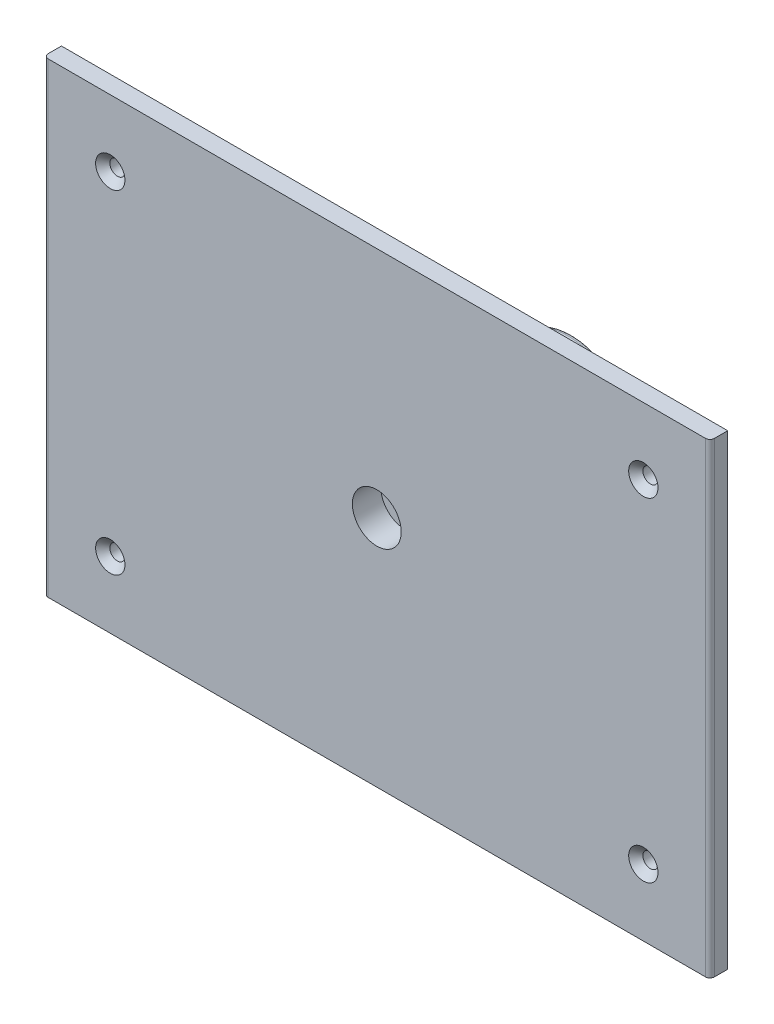
SolidWorks part; units mm, degrees
ref_plane "Front Plane" through (0, 0, 0) normal (0, 0, 1) x (1, 0, 0)
ref_plane "Top Plane" through (0, 0, 0) normal (0, 1, 0) x (1, 0, 0)
ref_plane "Right Plane" through (0, 0, 0) normal (1, 0, 0) x (0, 0, -1)
sketch "Sketch1" plane through (0, 0, 0) normal (0, 0, 1) x (1, 0, 0)
  line L1 (75, 52.5) -> (-75, 52.5)
  line L2 (75, 52.5) -> (75, -52.5)
  line L3 (75, -52.5) -> (-75, -52.5)
  line L4 (-75, 52.5) -> (-75, -52.5)
  line L5 (75, 52.5) -> (-75, -52.5) construction
  line L6 (75, -52.5) -> (-75, 52.5) construction
  point P0 (0, 0)
  dimension "D1" = 105
  dimension "D2" = 150
extrude "Boss-Extrude1" add sketch "Sketch1" along normal mid plane 4
hole_wizard "M3 Clearance Hole1" positions "Sketch3" profile "Sketch4" hole size "M3" standard "ISO" end condition through all
sketch "Sketch3" plane through (0, 0, -2) normal (0, 0, -1) x (-1, 0, 0)
  line L0 (0, 0) -> (0, 18.5081) construction
  line L2 (75, -52.5) -> (-75, -52.5) construction
  line L3 (-75, -52.5) -> (-75, 52.5) construction
  point P0 (-60, -37.5)
  point P2 (60, -37.5)
  dimension "D1" = 15
  dimension "D2" = 15
sketch "Sketch4" plane through (60, -37.5, -2) normal (1, 0, 0) x (0, 1, 0)
  line L0 (0, 0) -> (0, 4)
  line L1 (0, 4) -> (3.3, 4)
  line L2 (1.7, 2.4) -> (1.7, 0)
  line L5 (1.7, 0) -> (0, 0)
  line L7 (3.3, 4) -> (1.7, 2.4)
  line L8 (-3.3, 4) -> (-1.7, 2.4) construction
  line L11 (0, -6.35) -> (0, 107.95) construction
  dimension "Thru Hole Dia." = 3.4
  dimension "Thru Hole Depth" = 4
  dimension "Far C'Sink Dia." = 6.6
  dimension "Far C'Sink Angle" = 90
sketch "Sketch5" plane through (0, 0, -2) normal (0, 0, -1) x (-1, 0, 0)
  circle A0 centre (0, 0) radius 14
  dimension "D1" = 28
extrude "Boss-Extrude2" add sketch "Sketch5" along normal blind 40
hole_wizard "CBORE for M6 Hex Socket Head Cap Screw1" positions "Sketch6" profile "Sketch7" counterbore size "M6" standard "ISO" end condition up to next
sketch "Sketch6" plane through (0, 0, 2) normal (0, 0, 1) x (1, 0, 0)
  point P0 (0, 0)
sketch "Sketch7" plane through (0, 0, 2) normal (1, 0, 0) x (0, -1, 0)
  line L0 (0, 0) -> (0, 44)
  line L1 (0, 44) -> (3.3, 44)
  line L3 (3.3, 44) -> (3.3, 6.4)
  line L4 (3.3, 6.4) -> (5.5, 6.4)
  line L5 (5.5, 6.4) -> (5.5, 0)
  line L7 (5.5, 0) -> (0, 0)
  line L11 (0, -6.35) -> (0, 107.95) construction
  dimension "Thru Hole Dia." = 6.6
  dimension "Thru Hole Depth" = 44
  dimension "C'Bore Dia." = 11
  dimension "C'Bore Depth" = 6.4
mirror "Mirror1" about plane through (0, 0, 0) normal (0, 1, 0) of "M3 Clearance Hole1"
fillet "Fillet1" radius 1 1 edges at (-14, 0, -42)
fillet "Fillet2" radius 1 1 edges at (-14, 0, -2)
fillet "Fillet3" radius 1 2 edges at (-75, 0, 2) (75, 0, 2)
